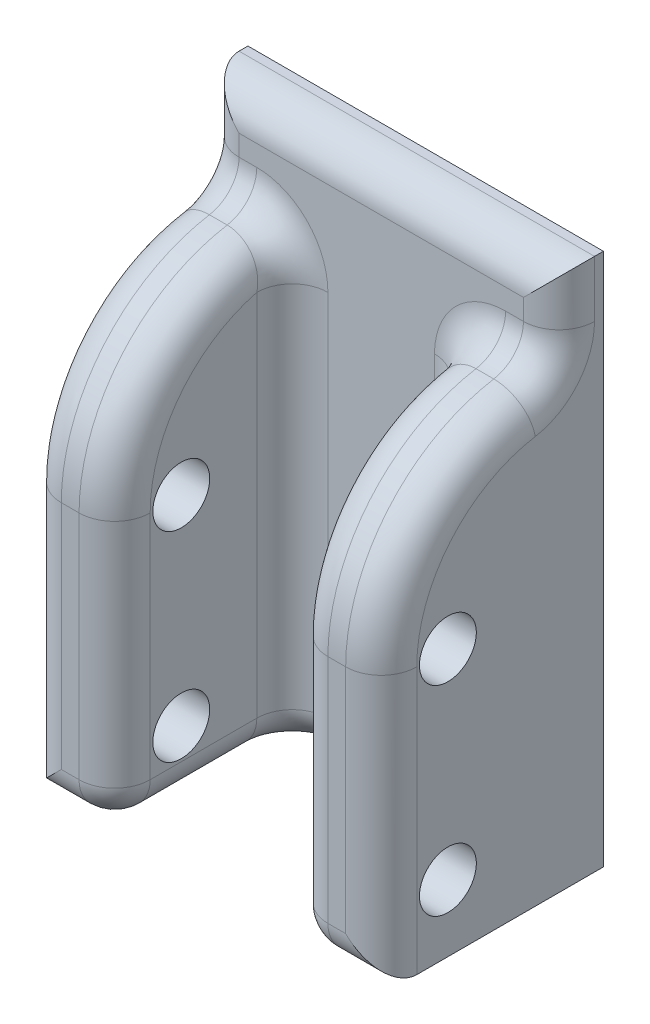
SolidWorks part; units mm, degrees
ref_plane "Front Plane" through (0, 0, 0) normal (0, 0, 1) x (1, 0, 0)
ref_plane "Top Plane" through (0, 0, 0) normal (0, 1, 0) x (1, 0, 0)
ref_plane "Right Plane" through (0, 0, 0) normal (1, 0, 0) x (0, 0, -1)
sketch "Sketch1" plane through (0, 0, 0) normal (0, 0, 1) x (1, 0, 0)
  line L1 (12.7, -19.05) -> (-12.7, -19.05)
  line L2 (12.7, -19.05) -> (12.7, 19.05)
  line L3 (12.7, 19.05) -> (-12.7, 19.05)
  line L4 (-12.7, -19.05) -> (-12.7, 19.05)
  circle A0 centre (-8.4667, 9.525) radius 2.032
  circle A1 centre (8.4667, 9.525) radius 2.032
  circle A2 centre (-8.4667, -9.525) radius 2.032
  circle A3 centre (8.4667, -9.525) radius 2.032
  point P0 (0, 0)
  point P14 (0, 0)
  point P15 (0, 0)
  point P16 (0, 19.05)
  point P17 (12.7, 0)
  dimension "D7" = 4.064
  dimension "D1" = 25.4
  dimension "D2" = 38.1
  dimension "D3" = 8.4667
  dimension "D4" = 9.525
  dimension "D5" = 9.525
  dimension "D6" = 8.4667
extrude "Boss-Extrude1" add sketch "Sketch1" along normal blind 3.175
sketch "Sketch2" plane through (-12.7, 0, 0) normal (-1, 0, 0) x (0, 0, 1)
  line L0 (3.175, 19.05) -> (3.175, -19.05) construction
  line L1 (3.175, 12.7) -> (3.175, -12.7)
  line L2 (3.175, 0) -> (15.875, 0) construction
  line L3 (15.875, 0) -> (15.875, -19.05)
  line L4 (15.875, -19.05) -> (3.175, -19.05)
  circle A1 centre (11.1125, 0) radius 2.032
  arc A2 (3.175, 12.7) -> (15.875, 0) centre (3.175, 0) cw
  circle A3 centre (11.1125, -14.2875) radius 2.032
  line M5 (3.175, -19.05) -> (3.175, 19.05)
  dimension "D3" = 4.064
  dimension "D1" = 12.7
  dimension "D2" = 4.7625
  dimension "D4" = 4.7625
  dimension "D5" = 4.7625
extrude "Boss-Extrude2" add sketch "Sketch2" against normal up to surface (25.4 mm away) contours L2 L4 L3 A1 M5 | L1 L2 A1 A2
sketch "Sketch3" plane through (0, 0, 3.175) normal (0, 0, 1) x (1, 0, 0)
  line L1 (-6.35, 12.7) -> (6.35, 12.7)
  line L2 (-6.35, 12.7) -> (-6.35, -19.05)
  line L3 (-6.35, -19.05) -> (6.35, -19.05)
  line L4 (6.35, 12.7) -> (6.35, -19.05)
  line L7 (-15.875, -19.05) -> (-12.7, -19.05)
  line L8 (-15.875, -19.05) -> (-15.875, 12.7)
  line L9 (-15.875, 12.7) -> (-12.7, 12.7)
  line L10 (-12.7, -19.05) -> (-12.7, 12.7)
  line L11 (15.875, 12.7) -> (12.7, 12.7)
  line L12 (15.875, 12.7) -> (15.875, -19.05)
  line L13 (15.875, -19.05) -> (12.7, -19.05)
  line L14 (12.7, 12.7) -> (12.7, -19.05)
  line L16 (-12.7, 0) -> (-12.7, -19.05) construction
  line L17 (12.7, -19.05) -> (-12.7, -19.05) construction
  line L18 (12.7, 12.7) -> (-12.7, 12.7) construction
  point P4 (0, 0)
  point P5 (0, 0)
  point P20 (0, 0)
  point P22 (0, 0)
  dimension "D1" = 9.525
  dimension "D2" = 9.525
  dimension "D3" = 6.35
  dimension "D4" = 12.7
extrude "Cut-Extrude1" cut sketch "Sketch3" along normal through all
fillet "Fillet1" radius 2.54 20 edges at (0, 19.05, 3.175) (12.7, 15.875, 3.175) (9.525, -19.05, 15.875) (12.7, -9.525, 15.875) (-12.7, -9.525, 15.875) (12.7, 8.9803, 12.1553) (9.525, 12.7, 3.175) (-12.7, 8.9803, 12.1553) (-12.7, 15.875, 3.175) (-9.525, 12.7, 3.175) (6.35, 8.9803, 12.1553) (-6.35, 8.9803, 12.1553) (-9.525, -19.05, 15.875) (-6.35, -3.175, 3.175) (6.35, -19.05, 9.525) (6.35, -3.175, 3.175) (6.35, -9.525, 15.875) (-6.35, -9.525, 15.875) (0, -19.05, 3.175) (-6.35, -19.05, 9.525)
equation "\"D3@Sketch3\"=\"D4@Sketch3\"/2"
equation "\"D1@Sketch3\"=\"D2@Sketch3\""
equation "\"D3@Sketch1\"=\"D1@Sketch1\"/3"
equation "\"D6@Sketch1\"=\"D1@Sketch1\"/3"
equation "\"D5@Sketch2\"=\"D4@Sketch2\""
